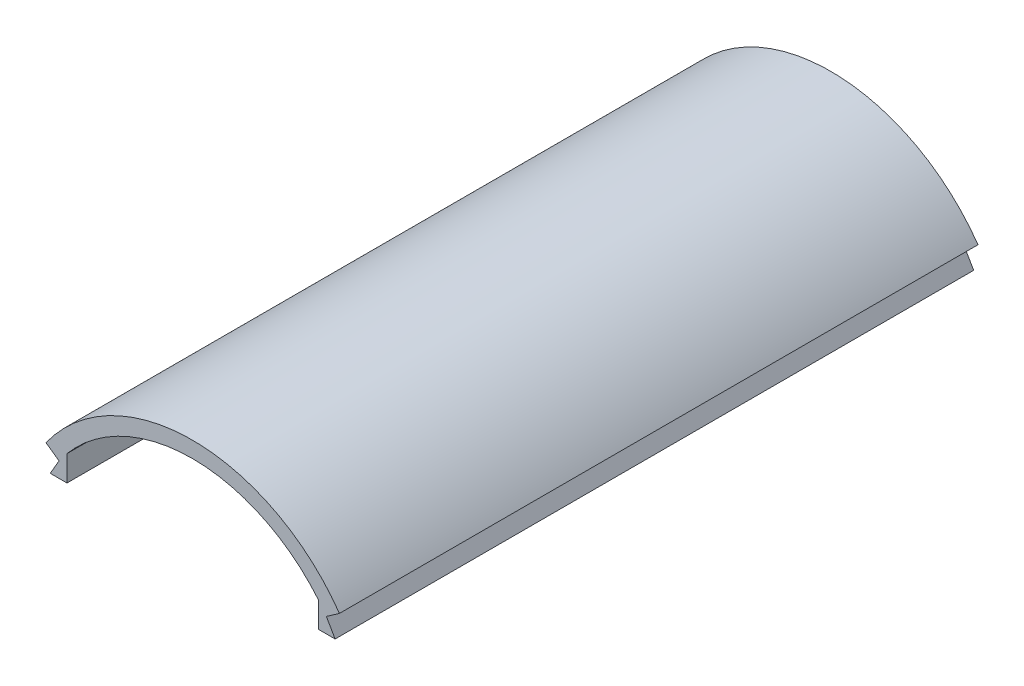
SolidWorks part; units mm, degrees
ref_plane "Front Plane" through (0, 0, 0) normal (0, 0, 1) x (1, 0, 0)
ref_plane "Top Plane" through (0, 0, 0) normal (0, 1, 0) x (1, 0, 0)
ref_plane "Right Plane" through (0, 0, 0) normal (1, 0, 0) x (0, 0, -1)
sketch "Sketch1" plane through (0, 0, 0) normal (0, 0, 1) x (1, 0, 0)
  circle A0 centre (0, 0) radius 22.5
  circle A1 centre (0, 0) radius 20.5
  dimension "D1" = 45
  dimension "D2" = 41
extrude "Boss-Extrude1" add sketch "Sketch1" along normal blind 80
sketch "Sketch2" plane through (0, 0, 80) normal (0, 0, 1) x (1, 0, 0)
  line L1 (-22.5, 0) -> (22.5, 0)
  line L2 (-22.5, 0) -> (-22.5, 22.5)
  line L3 (-22.5, 22.5) -> (22.5, 22.5)
  line L4 (22.5, 0) -> (22.5, 22.5)
  circle A0 centre (0, 0) radius 22.5 construction
extrude "Cut-Extrude1" cut sketch "Sketch2" against normal through all
sketch "Sketch4" plane through (0, 0, 80) normal (0, 0, 1) x (1, 0, 0)
  line L0 (19.1831, 11.7583) -> (18.4309, 12.9055)
  line L1 (16.7926, 11.7583) -> (18.4309, 12.9055)
  line L3 (20.5, 0) -> (22.5, 0)
  line L4 (16.7926, 11.7583) -> (19.1831, 11.7583)
  line L5 (18.4309, 12.9055) -> (16.7926, 11.7583)
  line L6 (15.7926, 11.7583) -> (15.7926, 9.7583)
  line L7 (19.1831, 11.7583) -> (14.7926, 11.7583)
  line L8 (19.1831, 11.7583) -> (19.1831, 8.7583)
  line L9 (19.1831, 8.7583) -> (14.7926, 8.7583)
  line L10 (14.7926, 11.7583) -> (14.7926, 8.7583)
  line L11 (15.7926, 9.7583) -> (18.0285, 9.7583)
  line L12 (16.7926, 11.7583) -> (15.7926, 11.7583)
  line L13 (14.7926, 8.7583) -> (18.5349, 8.7583)
  line L14 (14.7926, 8.7583) -> (14.7926, 11.7583)
  line L15 (14.7926, 11.7583) -> (16.7926, 11.7583)
  line L16 (-16.7023, 11.8863) -> (-18.3406, 13.0335)
  line L17 (-22.5, 0) -> (-20.5, 0) construction
  line L18 (-16.7023, 11.8863) -> (-15.7023, 11.8863)
  line L19 (-19.1041, 11.8863) -> (-14.7023, 11.8863)
  line L20 (-19.1041, 11.8863) -> (-19.1041, 8.8863)
  line L21 (-19.1041, 8.8863) -> (-14.7023, 8.8863)
  line L22 (-14.7023, 11.8863) -> (-14.7023, 8.8863)
  line L23 (-14.7023, 11.8863) -> (-15.7023, 11.8863)
  line L24 (-14.7023, 11.8863) -> (-14.7023, 8.8863)
  line L25 (-14.7023, 8.8863) -> (-15.7023, 8.8863)
  line L26 (-15.7023, 11.8863) -> (-15.7023, 8.8863)
  line L27 (-19.1041, 8.8863) -> (-14.7023, 8.8863)
  line L28 (-19.1041, 8.8863) -> (-19.1041, 9.8863)
  line L29 (-19.1041, 9.8863) -> (-14.7023, 9.8863)
  line L30 (-14.7023, 8.8863) -> (-14.7023, 9.8863)
  line L31 (-15.7023, 11.8863) -> (-15.7023, 9.8863)
  line L32 (-15.7023, 9.8863) -> (-17.9586, 9.8863)
  line L33 (-16.7023, 11.8863) -> (-15.7023, 11.1746)
  line L34 (-15.7023, 11.1746) -> (-15.7023, 9.8863)
  line L35 (-15.7023, 9.8863) -> (-17.9586, 9.8863)
  line L36 (-16.7023, 11.8863) -> (-19.1041, 11.8863)
  line L37 (-19.1041, 11.8863) -> (-19.1041, 8.8863)
  line L38 (-19.1041, 8.8863) -> (-18.4739, 8.8863)
  line L39 (-22.5, 0) -> (-20.5, 0)
  line L40 (-16.7023, 11.8863) -> (-15.7023, 11.8863)
  line L41 (-15.7023, 9.8863) -> (-17.9586, 9.8863)
  arc A0 (22.5, 0) -> (18.4309, 12.9055) centre (0, 0) ccw
  arc A1 (20.5, 0) -> (16.7926, 11.7583) centre (0, 0) ccw
  arc A2 (18.0285, 9.7583) -> (16.7926, 11.7583) centre (0, 0) ccw
  arc A3 (18.5349, 8.7583) -> (16.7926, 11.7583) centre (0, 0) ccw
  arc A4 (-22.5, 0) -> (-18.3406, 13.0335) centre (0, 0) cw
  arc A5 (-20.5, 0) -> (-16.7023, 11.8863) centre (0, 0) cw
  arc A6 (-17.9586, 9.8863) -> (-16.7023, 11.8863) centre (0, 0) cw
  arc A7 (-18.4739, 8.8863) -> (-16.7023, 11.8863) centre (0, 0) cw
  arc A8 (-17.9586, 9.8863) -> (-16.7023, 11.8863) centre (0, 0) cw
  line M11 (22.5, 0) -> (20.5, 0)
  dimension "D1" = 35
  dimension "D7" = 35
  dimension "D2" = 2
  dimension "D3" = 3
  dimension "D4" = 2
  dimension "D5" = 1
  dimension "D6" = 1
  dimension "D8" = 3
  dimension "D9" = 1
  dimension "D10" = 1
  dimension "D11" = 1
extrude "Boss-Extrude2" add sketch "Sketch4" against normal up to surface (80 mm away) separate body contours A1 A0 L8 L9 M11 | L1 L4 L0 | A1 L9 L8 L4 | L9 A1 L11 L6 L7 L10 | L16 A4 L39 A5 | L28 L27 L30 L29 | L24 L23 L26 L25 up to face at (0, -10.75, 0)
sketch "Sketch5" plane through (0, 0, 80) normal (0, 0, 1) x (1, 0, 0)
  line L0 (16.7926, 11.7583) -> (18.4309, 12.9055) construction
  line L1 (-16.7023, 11.8863) -> (-18.3406, 13.0335) construction
  line L2 (16.7926, 11.7583) -> (18.4309, 12.9055)
  line L3 (-18.3406, 13.0335) -> (-16.7023, 11.8863)
  line L4 (-15.7023, 9.9863) -> (-17.7992, 9.9863)
  line L5 (-15.7023, 11.8863) -> (-15.7023, 9.8863) construction
  line L6 (-17.7992, 9.9863) -> (-16.7023, 11.8863)
  line L7 (-15.7023, 11.8863) -> (-15.7023, 9.9863)
  line L8 (-15.7023, 11.8863) -> (-16.7023, 11.8863)
  line L9 (-17.9586, 9.8863) -> (-15.7023, 9.8863) construction
  line L10 (-15.7023, 11.8863) -> (-16.7023, 11.8863)
  line L11 (-15.7023, 11.8863) -> (-15.7023, 13.8432)
  line L12 (-15.7023, 13.8432) -> (-16.7023, 13.8432)
  line L13 (-16.7023, 11.8863) -> (-16.7023, 13.8432)
  line L14 (16.7926, 11.7583) -> (15.7926, 11.7583)
  line L15 (15.7926, 11.7583) -> (15.7926, 9.7583) construction
  line L16 (15.7926, 11.7583) -> (15.7926, 9.8583)
  line L17 (15.7926, 9.8583) -> (17.8896, 9.8583)
  line L18 (17.8896, 9.8583) -> (16.7926, 11.7583)
  line L19 (15.7926, 9.7583) -> (18.0285, 9.7583) construction
  line L21 (15.7926, 11.7583) -> (16.7926, 11.7583)
  line L22 (15.7926, 11.7583) -> (15.7926, 14.392)
  line L23 (15.7926, 14.392) -> (16.7926, 14.392)
  line L24 (16.7926, 11.7583) -> (16.7926, 14.392)
  arc A0 (-16.7023, 11.8863) -> (16.7926, 11.7583) centre (0, 0) cw
  arc A1 (-18.3406, 13.0335) -> (18.4309, 12.9055) centre (0, 0) cw
  arc A2 (-18.3406, 13.0335) -> (-22.5, 0) centre (0, 0) ccw construction
  line M14 (18.4309, 12.9055) -> (16.7926, 11.7583)
  line M17 (15.7926, 9.7583) -> (15.7926, 11.7583)
  dimension "D1" = 60
  dimension "D2" = 0.1
  dimension "D3" = 60
  dimension "D4" = 0.1
extrude "Boss-Extrude3" add sketch "Sketch5" against normal up to surface (80 mm away) contours A1 L3 L13 L12 L11 A0 L22 L23 L24 M14 | A0 L22 L14 | L22 A0 L24 L23 | L17 L18 L14 M17 | L7 L8 L6 L4 | A0 L8 L11 | L13 A0 L11 L12 up to face at (17.8607, 8.848, 0)
sketch "Sketch6" plane through (0, 0, 80) normal (0, 0, 1) x (1, 0, 0)
  line L0 (18.5349, 8.7583) -> (14.7926, 8.7583) construction
  line L1 (14.7926, 11.7583) -> (15.7926, 11.7583)
  line L2 (14.7926, 11.7583) -> (14.7926, 8.7583)
  line L3 (14.7926, 8.7583) -> (15.7926, 8.7583)
  line L4 (15.7926, 11.7583) -> (15.7926, 8.7583)
  line L5 (-16.7023, 11.8863) -> (-18.3318, 13.0459)
  line L6 (15.7926, 9.7583) -> (19.1614, 9.7583)
  line L7 (15.7926, 9.7583) -> (15.7926, 8.7583)
  line L8 (15.7926, 8.7583) -> (19.1614, 8.7583)
  line L9 (19.1614, 9.7583) -> (19.1614, 8.7583)
  line L10 (-14.7023, 8.8863) -> (-15.7023, 8.8863)
  line L11 (-14.7023, 8.8863) -> (-14.7023, 11.8863)
  line L12 (-14.7023, 11.8863) -> (-15.7023, 11.8863)
  line L13 (-15.7023, 8.8863) -> (-15.7023, 11.8863)
  line L14 (-15.7023, 9.8863) -> (-19.4266, 9.8863)
  line L15 (-15.7023, 9.8863) -> (-15.7023, 8.8863)
  line L16 (-15.7023, 8.8863) -> (-19.4266, 8.8863)
  line L17 (-19.4266, 9.8863) -> (-19.4266, 8.8863)
  line L18 (16.7926, 11.7583) -> (18.4309, 12.9055)
  arc A0 (-16.7023, 11.8863) -> (16.7926, 11.7583) centre (0, 0) ccw
  arc A1 (18.4309, 12.9055) -> (-22.5, 0) centre (0, 0) ccw construction
  arc A2 (18.4309, 12.9055) -> (-18.3318, 13.0459) centre (0, 0) cw
  line M1 (-14.7023, 11.8863) -> (-15.7023, 11.8863)
  line M5 (15.7926, 11.7583) -> (14.7926, 11.7583)
  line M6 (14.7926, 11.7583) -> (14.7926, 8.7583)
  line M7 (14.7926, 8.7583) -> (18.5349, 8.7583)
  arc M8 (18.5349, 8.7583) -> (20.5, 0) centre (0, 0) cw
  line M9 (20.5, 0) -> (22.5, 0)
  arc M10 (22.5, 0) -> (19.1831, 11.7583) centre (0, 0) ccw
  line M11 (19.1831, 11.7583) -> (18.4309, 12.9055)
  arc M12 (18.4309, 12.9055) -> (-22.5, 0) centre (0, 0) ccw
  line M13 (-22.5, 0) -> (-20.5, 0)
  arc M14 (-20.5, 0) -> (-18.4739, 8.8863) centre (0, 0) cw
  line M15 (-18.4739, 8.8863) -> (-14.7023, 8.8863)
  line M16 (-14.7023, 8.8863) -> (-14.7023, 11.8863)
  line M18 (-15.7023, 9.9863) -> (-15.7023, 9.8863)
  line M19 (-15.7023, 9.8863) -> (-17.9586, 9.8863)
  arc M20 (-17.9586, 9.8863) -> (-16.7023, 11.8863) centre (0, 0) cw
  arc M23 (16.7926, 11.7583) -> (18.0285, 9.7583) centre (0, 0) cw
  line M24 (18.0285, 9.7583) -> (15.7926, 9.7583)
  line M25 (15.7926, 9.7583) -> (15.7926, 9.8583)
extrude "Cut-Extrude2" cut sketch "Sketch6" against normal through all contours L17 L14 L5 L16 M20 M12 M13 M14 | A2 A0 M9 M13 | A0 L14 L17 L16 | A0 L13 M19 M15 | L13 M15 M16 M1 M18 | L4 M5 M6 M7 M25 | A0 L4 M7 M24 | A0 L8 L9 L6 | L18 L6 L9 L8 M23 M8 M9 M10 M11
